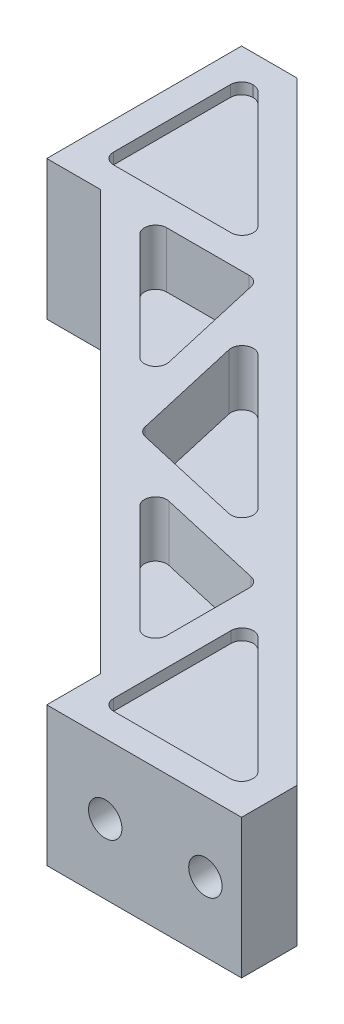
SolidWorks part; units mm, degrees
ref_plane "Front Plane" through (0, 0, 0) normal (0, 0, 1) x (1, 0, 0)
ref_plane "Top Plane" through (0, 0, 0) normal (0, 1, 0) x (1, 0, 0)
ref_plane "Right Plane" through (0, 0, 0) normal (1, 0, 0) x (0, 0, -1)
sketch "Sketch1" plane through (0, 0, 0) normal (0, 1, 0) x (1, 0, 0)
  line L3 (0, 120) -> (10, 120)
  line L4 (10, 120) -> (120, 10)
  line L5 (120, 10) -> (120, 0)
  line L6 (9.6447, 85) -> (85, 9.6447)
  line L7 (0, 0) -> (0, 85) construction
  line L8 (85, 9.6447) -> (85, 0)
  line L9 (9.6447, 85) -> (0, 85)
  line L10 (0, 120) -> (0, 85)
  line L11 (85, 0) -> (120, 0)
  line L12 (85, 0) -> (0, 0) construction
  dimension "D1" = 120
  dimension "D2" = 25
  dimension "D3" = 10
  dimension "D4" = 35
extrude "Boss-Extrude1" add sketch "Sketch1" along normal mid plane 25
sketch "Sketch2" plane through (0, 0, 0) normal (0, 0, 1) x (1, 0, 0)
  line L0 (120, 5) -> (89, 5)
  line L1 (120, 12.5) -> (120, -12.5) construction
  line L2 (89, 5) -> (89, -5)
  line L3 (89, -5) -> (120, -5)
  line L4 (120, 0) -> (85, 0) construction
  line L9 (85, -12.5) -> (120, -12.5)
  line L10 (120, -12.5) -> (120, 12.5)
  line L11 (120, 12.5) -> (85, 12.5)
  line L15 (85, 12.5) -> (85, -12.5) construction
  line L16 (85, 12.5) -> (85, -12.5)
  line L17 (85, -12.5) -> (120, -12.5) construction
  line L18 (120, -12.5) -> (120, 12.5) construction
  line L19 (120, 12.5) -> (85, 12.5) construction
  line L20 (85, 12.5) -> (85, -12.5) construction
  dimension "D2" = 10
  dimension "D3" = 4
  dimension "D1" = 0
extrude "Cut-Extrude1" cut sketch "Sketch2" against normal through all from offset 10 offset against normal yes
ref_plane "Plane1" through (0, 0, 0) normal (0.7071, 0, 0.7071) x (0.7071, 0, -0.7071)
sketch "Sketch3" plane through (0, -12.5, 0) normal (0, -1, 0) x (1, 0, 0)
  line L0 (44.5764, -78.3525) -> (37.9289, -85) construction
  line L1 (120, -10) -> (10, -120) construction
  line L2 (47.3223, -47.3223) -> (65, -65) construction
  line L6 (9.6447, -85) -> (85, -9.6447) construction
  line L7 (78.3525, -44.5764) -> (85, -37.9289) construction
  line L8 (0, -85) -> (9.6447, -85) construction
  line L9 (57.5054, -44.2103) -> (85, -16.7157)
  line L10 (85, -37.9289) -> (57.5054, -44.2103)
  line L14 (16.7157, -85) -> (37.9289, -85)
  line L15 (44.5764, -78.3525) -> (78.3525, -44.5764)
  line L16 (78.3525, -44.5764) -> (50.8579, -50.8579)
  line L18 (85, -16.7157) -> (85, -37.9289)
  line L19 (44.2103, -57.5054) -> (57.5054, -44.2103) construction
  line L20 (44.5764, -78.3525) -> (50.8579, -50.8579)
  line L22 (37.9289, -85) -> (44.2103, -57.5054)
  line L31 (44.2103, -57.5054) -> (16.7157, -85)
  point P24 (61.4645, -61.4645)
  dimension "D2" = 5
  dimension "D3" = 5
  dimension "D1" = 5
extrude "Cut-Extrude2" cut sketch "Sketch3" against normal blind 10
sketch "Sketch4" plane through (0, -12.5, 0) normal (0, -1, 0) x (1, 0, 0)
  line L1 (9.6447, -85) -> (85, -9.6447) construction
  line L2 (120, -10) -> (10, -120) construction
  line L3 (0, -85) -> (45, -85) construction
  line L7 (45, -85) -> (10, -120) construction
  line L14 (47.3223, -47.3223) -> (65, -65) construction
  line L20 (10, -120) -> (0, -120) construction
  line L21 (0, -120) -> (0, -85) construction
  line L22 (5, -90) -> (32.9289, -90)
  line L23 (32.9289, -90) -> (7.9289, -115)
  line L24 (7.9289, -115) -> (5, -115)
  line L25 (5, -115) -> (5, -90)
  line L26 (120, 0) -> (85, 0) construction
  line L27 (120, -10) -> (120, 0) construction
  line L28 (85, -45) -> (120, -10) construction
  line L29 (85, 0) -> (85, -45) construction
  line L30 (115, -5) -> (90, -5)
  line L31 (115, -7.9289) -> (115, -5)
  line L32 (90, -32.9289) -> (115, -7.9289)
  line L33 (90, -5) -> (90, -32.9289)
  dimension "D1" = 5
extrude "Cut-Extrude3" cut sketch "Sketch4" against normal blind 2
fillet "Fillet3" radius 2 17 edges at (44.5764, -7.5, -78.3525) (16.7157, -7.5, -85) (37.9289, -7.5, -85) (44.2103, -7.5, -57.5054) (85, -7.5, -37.9289) (85, -7.5, -16.7157) (57.5054, -7.5, -44.2103) (50.8579, -7.5, -50.8579) (78.3525, -7.5, -44.5764) (90, -11.5, -32.9289) (115, -11.5, -7.9289) (115, -11.5, -5) (90, -11.5, -5) (5, -11.5, -115) (7.9289, -11.5, -115) (32.9289, -11.5, -90) (5, -11.5, -90)
mirror "Mirror2" about plane through (0, 0, 0) normal (0, 1, 0) of "Fillet3", "Cut-Extrude2", "Cut-Extrude3"
sketch "Sketch6" plane through (0, 0, -10) normal (0, 0, -1) x (-1, 0, 0)
  line L0 (-120, 0) -> (-89, 0) construction
  line L1 (-120, -5) -> (-120, 5) construction
  line L3 (-104.5, 5) -> (-104.5, -5) construction
  line L4 (-120, 5) -> (-89, 5) construction
  line L5 (-89, -5) -> (-120, -5) construction
  line L7 (-89, 5) -> (-89, -5) construction
  circle A0 centre (-113.5, 0) radius 3
  circle A1 centre (-95.5, 0) radius 3
  dimension "5.5" = 6
  dimension "D1" = 18
extrude "Cut-Extrude5" cut sketch "Sketch6" against normal through all
fillet "Fillet4" radius 3 2 edges at (89, -5, -25.5) (89, 5, -25.5)
mirror "Mirror3" about plane through (0, 0, 0) normal (0.7071, 0, 0.7071) of "Fillet4", "Cut-Extrude1", "Cut-Extrude5"
